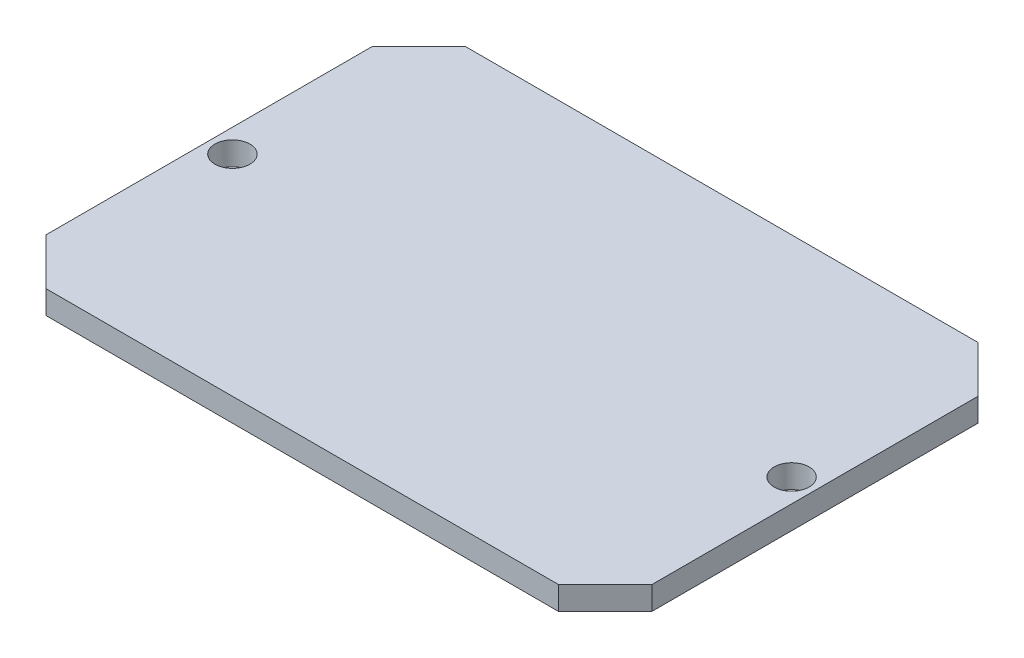
SolidWorks part; units mm, degrees
ref_plane "Front Plane" through (0, 0, 0) normal (0, 0, 1) x (1, 0, 0)
ref_plane "Top Plane" through (0, 0, 0) normal (0, 1, 0) x (1, 0, 0)
ref_plane "Right Plane" through (0, 0, 0) normal (1, 0, 0) x (0, 0, -1)
sketch "Sketch1" plane through (0, 0, 0) normal (0, 1, 0) x (1, 0, 0)
  line L0 (41.275, 0) -> (38.1, 0) construction
  line L1 (-31.75, 28.575) -> (31.75, 28.575)
  line L2 (-41.275, 19.05) -> (-41.275, -19.05)
  line L3 (-31.75, -28.575) -> (31.75, -28.575)
  line L4 (41.275, 19.05) -> (41.275, -19.05)
  circle A0 centre (38.1, 0) radius 2.3825
  circle A1 centre (-38.1, 0) radius 2.3825
  arc A2 (31.75, 28.575) -> (41.275, 19.05) centre (31.75, 19.05) cw
  arc A3 (-41.275, 19.05) -> (-31.75, 28.575) centre (-31.75, 19.05) cw
  arc A4 (-31.75, -28.575) -> (-41.275, -19.05) centre (-31.75, -19.05) cw
  arc A5 (41.275, -19.05) -> (31.75, -28.575) centre (31.75, -19.05) cw
  point P0 (0, 0)
  dimension "D1" = 9.525
  dimension "D2" = 4.765
extrude "Extrude1" add sketch "Sketch1" along normal blind 3.175
sketch "Sketch2" plane through (0, 0, 0) normal (0, 1, 0) x (1, 0, 0)
  line L0 (31.75, 28.575) -> (41.275, 19.05)
  line L1 (41.275, 19.05) -> (41.275, 28.575)
  line L2 (41.275, 28.575) -> (31.75, 28.575)
  line L3 (-31.75, 28.575) -> (-41.275, 19.05)
  line L4 (-41.275, 19.05) -> (-41.275, 28.575)
  line L5 (-41.275, 28.575) -> (-31.75, 28.575)
  line L6 (-41.275, -19.05) -> (-31.75, -28.575)
  line L7 (-31.75, -28.575) -> (-41.275, -28.575)
  line L8 (-41.275, -28.575) -> (-41.275, -19.05)
  line L9 (41.275, -19.05) -> (31.75, -28.575)
  line L10 (31.75, -28.575) -> (41.275, -28.575)
  line L11 (41.275, -28.575) -> (41.275, -19.05)
extrude "Extrude2" add sketch "Sketch2" along normal blind 3.175
chamfer "Chamfer1" distance 6.35 angle 45 4 edges at (41.275, 1.5875, 28.575) (-41.275, 1.5875, 28.575) (-41.275, 1.5875, -28.575) (41.275, 1.5875, -28.575)
